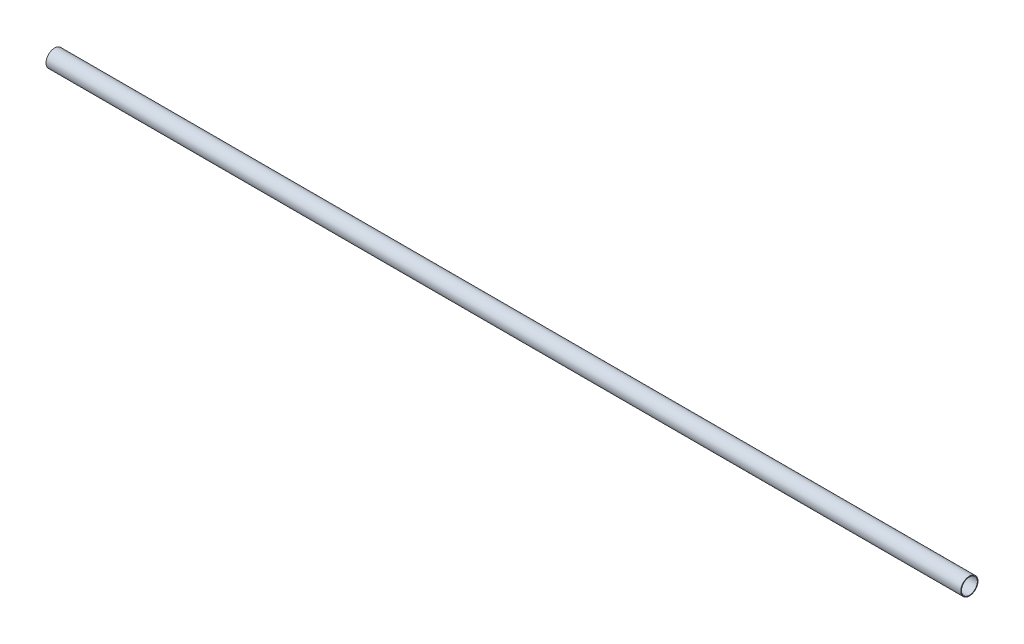
SolidWorks part; units mm, degrees
material "Acero al carbono no aleado"
ref_plane "Alzado" through (0, 0, 0) normal (0, 0, 1) x (1, 0, 0)
ref_plane "Planta" through (0, 0, 0) normal (0, 1, 0) x (1, 0, 0)
ref_plane "Vista lateral" through (0, 0, 0) normal (1, 0, 0) x (0, 0, -1)
sketch "Croquis1" plane through (0, 0, 0) normal (1, 0, 0) x (0, 0, -1)
  circle A0 centre (0, 0) radius 25.4
  circle A1 centre (0, 0) radius 23.4
  dimension "D1" = 50.8
  dimension "D2" = 2
extrude "Saliente-Extruir1" add sketch "Croquis1" along normal mid plane 2700
